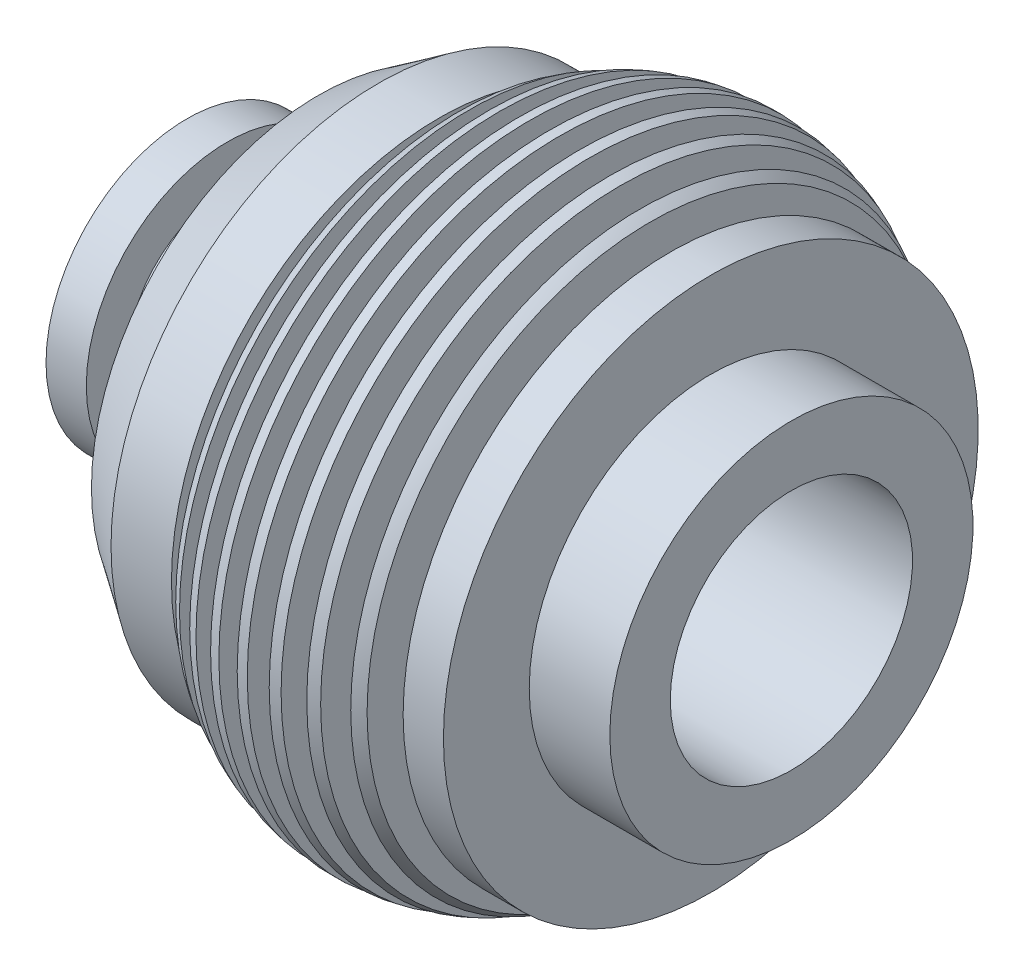
SolidWorks part; units mm, degrees
ref_plane "Front Plane" through (0, 0, 0) normal (0, 0, 1) x (1, 0, 0)
ref_plane "Top Plane" through (0, 0, 0) normal (0, 1, 0) x (1, 0, 0)
ref_plane "Right Plane" through (0, 0, 0) normal (1, 0, 0) x (0, 0, -1)
sketch "Sketch1" plane through (0, 0, 0) normal (0, 0, 1) x (1, 0, 0)
  line L0 (-21.6792, 0) -> (0, 0)
  line L1 (0, 0) -> (0, 15.0655)
  line L2 (0, 15.0655) -> (100, 15.0655)
  line L3 (100, 15.0655) -> (100, 30.0655)
  line L4 (100, 30.0655) -> (80, 30.0655)
  line L5 (80, 30.0655) -> (80, 51.3655)
  line L6 (80, 51.3655) -> (70, 51.3655)
  line L7 (12.5, 51.3655) -> (-2.5, 51.3655)
  line L8 (-2.5, 51.3655) -> (-17.4227, 41.3)
  line L9 (-17.4227, 41.3) -> (-17.4227, 20)
  line L10 (-27.4227, 10) -> (-40, 10)
  line L12 (-40, 20) -> (-50, 20)
  line L13 (-50, 20) -> (-50, 0)
  line L14 (-50, 0) -> (-21.6792, 0)
  line L15 (-50, -15) -> (100, -15) construction
  line L16 (-40, 20) -> (-40, 10)
  line L17 (12.5, 51.3655) -> (12.5, 35.0655)
  line L18 (12.5, 35.0655) -> (17.5, 35.0655)
  line L19 (70, 35.0655) -> (70, 51.3655)
  line L20 (20, 35.0655) -> (25, 35.0655)
  line L21 (12.5, 35.0655) -> (17.5, 35.0655)
  line L22 (12.5, 35.0655) -> (12.5, 51.3655)
  line L24 (17.5, 35.0655) -> (17.5, 55.3102)
  line L25 (42.5, 35.0655) -> (47.5, 35.0655)
  line L26 (42.5, 35.0655) -> (42.5, 62.5471)
  line L28 (47.5, 35.0655) -> (47.5, 62.1034)
  line L30 (47.5, 35.0655) -> (47.5, 62.1034)
  line L32 (50, 35.0655) -> (50, 61.655)
  line L33 (50, 35.0655) -> (55, 35.0655)
  line L34 (50, 35.0655) -> (50, 61.655)
  line L36 (55, 35.0655) -> (55, 60.2798)
  line L38 (55, 35.0655) -> (55, 60.2798)
  line L40 (57.5, 35.0655) -> (57.5, 59.3362)
  line L41 (57.5, 35.0655) -> (62.5, 35.0655)
  line L42 (57.5, 35.0655) -> (57.5, 59.3362)
  line L44 (62.5, 35.0655) -> (62.5, 56.8716)
  line L46 (62.5, 35.0655) -> (62.5, 56.8716)
  line L48 (65, 35.0655) -> (65, 55.3102)
  line L49 (65, 35.0655) -> (70, 35.0655)
  line L50 (65, 35.0655) -> (65, 55.3102)
  line L52 (70, 35.0655) -> (70, 51.3655)
  line L54 (40, 35.0655) -> (40, 62.5471)
  line L56 (42.5, 35.0655) -> (42.5, 62.5471)
  line L57 (35, 35.0655) -> (40, 35.0655)
  line L58 (35, 35.0655) -> (35, 62.1034)
  line L60 (40, 35.0655) -> (40, 62.5471)
  line L62 (32.5, 35.0655) -> (32.5, 61.655)
  line L64 (35, 35.0655) -> (35, 62.1034)
  line L65 (27.5, 35.0655) -> (32.5, 35.0655)
  line L66 (27.5, 35.0655) -> (27.5, 60.2798)
  line L68 (32.5, 35.0655) -> (32.5, 61.655)
  line L69 (20, 35.0655) -> (25, 35.0655)
  line L70 (17.5, 35.0655) -> (17.5, 55.3102)
  line L72 (27.5, 35.0655) -> (27.5, 60.2798)
  line L74 (25, 35.0655) -> (25, 59.3362)
  line L76 (27.5, 35.0655) -> (27.5, 60.2798)
  line L77 (20, 35.0655) -> (25, 35.0655)
  line L78 (20, 35.0655) -> (20, 56.8716)
  line L80 (25, 35.0655) -> (25, 59.3362)
  line L82 (17.5, 35.0655) -> (17.5, 55.3102)
  line L84 (20, 35.0655) -> (20, 56.8716)
  line L85 (27.5, 35.0655) -> (32.5, 35.0655)
  line L86 (35, 35.0655) -> (40, 35.0655)
  line L87 (42.5, 35.0655) -> (47.5, 35.0655)
  line L88 (50, 35.0655) -> (55, 35.0655)
  line L89 (57.5, 35.0655) -> (62.5, 35.0655)
  line L90 (65, 35.0655) -> (70, 35.0655)
  arc A1 (-17.4227, 20) -> (-27.4227, 10) centre (-27.4227, 20) cw
  arc A2 (17.5, 55.3102) -> (20, 56.8716) centre (41.25, 20.0655) cw
  arc A3 (62.5, 56.8716) -> (65, 55.3102) centre (41.25, 20.0655) cw
  arc A4 (55, 60.2798) -> (57.5, 59.3362) centre (41.25, 20.0655) cw
  arc A5 (47.5, 62.1034) -> (50, 61.655) centre (41.25, 20.0655) cw
  arc A6 (40, 62.5471) -> (42.5, 62.5471) centre (41.25, 20.0655) cw
  arc A7 (32.5, 61.655) -> (35, 62.1034) centre (41.25, 20.0655) cw
  arc A8 (25, 59.3362) -> (27.5, 60.2798) centre (41.25, 20.0655) cw
  point P44 (41.1057, 35.0655)
  point P45 (48.5498, 34.1635)
  point P48 (63.3632, 35.0655)
  point P49 (67.2015, 35.0655)
  dimension "D6" = 42.5
  dimension "D14" = 10
  dimension "D1" = 50
  dimension "D2" = 100
  dimension "D3" = 15
  dimension "D4" = 20
  dimension "D5" = 10
  dimension "D7" = 36.3
  dimension "D8" = 15
  dimension "D9" = 20
  dimension "D10" = 10
  dimension "D11" = 15
  dimension "D12" = 10
  dimension "D13" = 146
  dimension "D15" = 21.3
  dimension "D16" = 18
  dimension "D17" = 20
  dimension "D18" = 5
  dimension "D19" = 5
  dimension "D20" = 2.5
  dimension "D21" = 5
  dimension "D22" = 2.5
  dimension "D23" = 2.5
  dimension "D24" = 5
  dimension "D25" = 2.5
  dimension "D26" = 5
  dimension "D27" = 2.5
  dimension "D28" = 5
  dimension "D29" = 2.5
  dimension "D30" = 5
  dimension "D31" = 5
  dimension "D32" = 2.5
revolve "Revolve1" add sketch "Sketch1" angle 360 about L15
